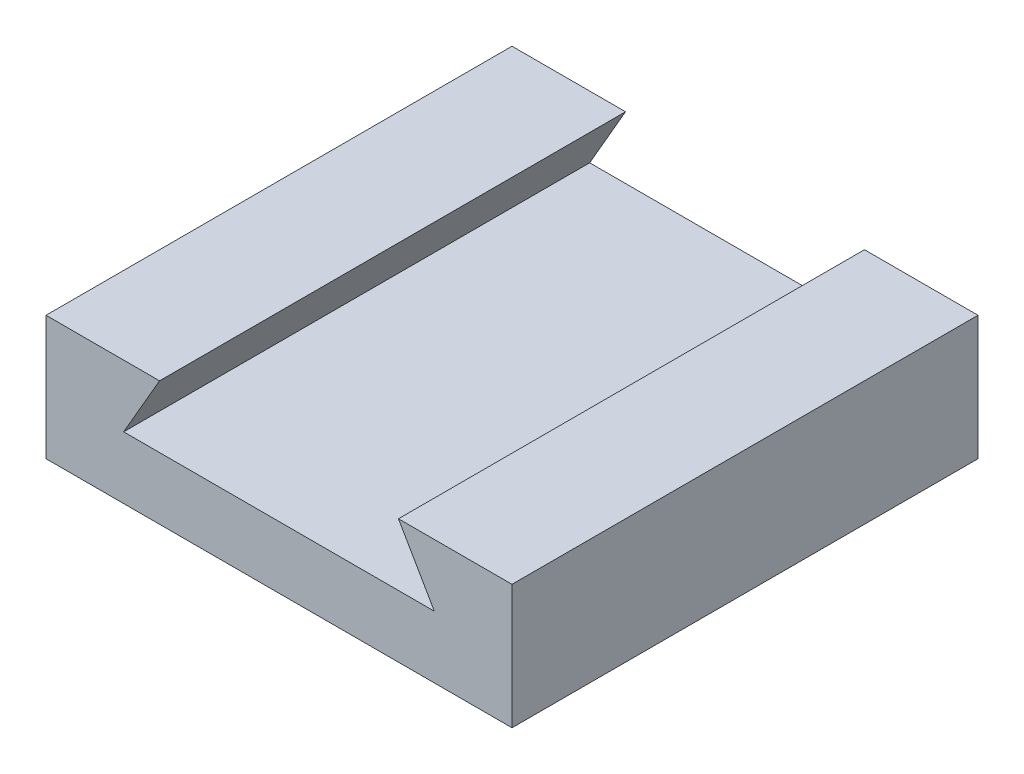
SolidWorks part; units mm, degrees
ref_plane "Спереди" through (0, 0, 0) normal (0, 0, 1) x (1, 0, 0)
ref_plane "Сверху" through (0, 0, 0) normal (0, 1, 0) x (1, 0, 0)
ref_plane "Справа" through (0, 0, 0) normal (1, 0, 0) x (0, 0, -1)
sketch "Эскиз1" plane through (0, 0, 0) normal (0, 0, 1) x (1, 0, 0)
  line L0 (0, 0) -> (0, 8)
  line L1 (0, 8) -> (30, 8)
  line L2 (30, 8) -> (30, 0)
  line L3 (30, 0) -> (0, 0)
  dimension "D1" = 30
  dimension "D2" = 8
extrude "Бобышка-Вытянуть1" add sketch "Эскиз1" along normal blind 30
sketch "Эскиз2" plane through (0, 0, 30) normal (0, 0, 1) x (1, 0, 0)
  line L0 (7.3094, 8) -> (5, 4)
  line L1 (30, 8) -> (0, 8) construction
  line L2 (5, 4) -> (25, 4)
  line L3 (25, 4) -> (22.6906, 8)
  line L4 (22.6906, 8) -> (7.3094, 8)
  line L5 (30, 0) -> (30, 8) construction
  dimension "D1" = 4
  dimension "D2" = 60
  dimension "D3" = 60
  dimension "D4" = 20
  dimension "D5" = 5
extrude "Вырез-Вытянуть1" cut sketch "Эскиз2" against normal through all
sketch "Эскиз3" plane through (0, 0, 30) normal (0, 0, 1) x (1, 0, 0)
  line L0 (0, 3) -> (2.8868, 8)
  line L1 (0, 8) -> (0, 0) construction
  line L2 (30, 8) -> (22.6906, 8) construction
  line L3 (2.8868, 8) -> (0, 8)
  line L4 (0, 8) -> (0, 3)
  line L5 (26.3453, 8) -> (26.3453, 1.7771) construction
  line L6 (52.6906, 8) -> (52.6906, 3)
  line L7 (52.6906, 3) -> (49.8038, 8)
  line L8 (49.8038, 8) -> (52.6906, 8)
  dimension "D1" = 60
  dimension "D2" = 5
extrude "Вырез-Вытянуть2" [suppressed] cut sketch "Эскиз3" against normal through all
